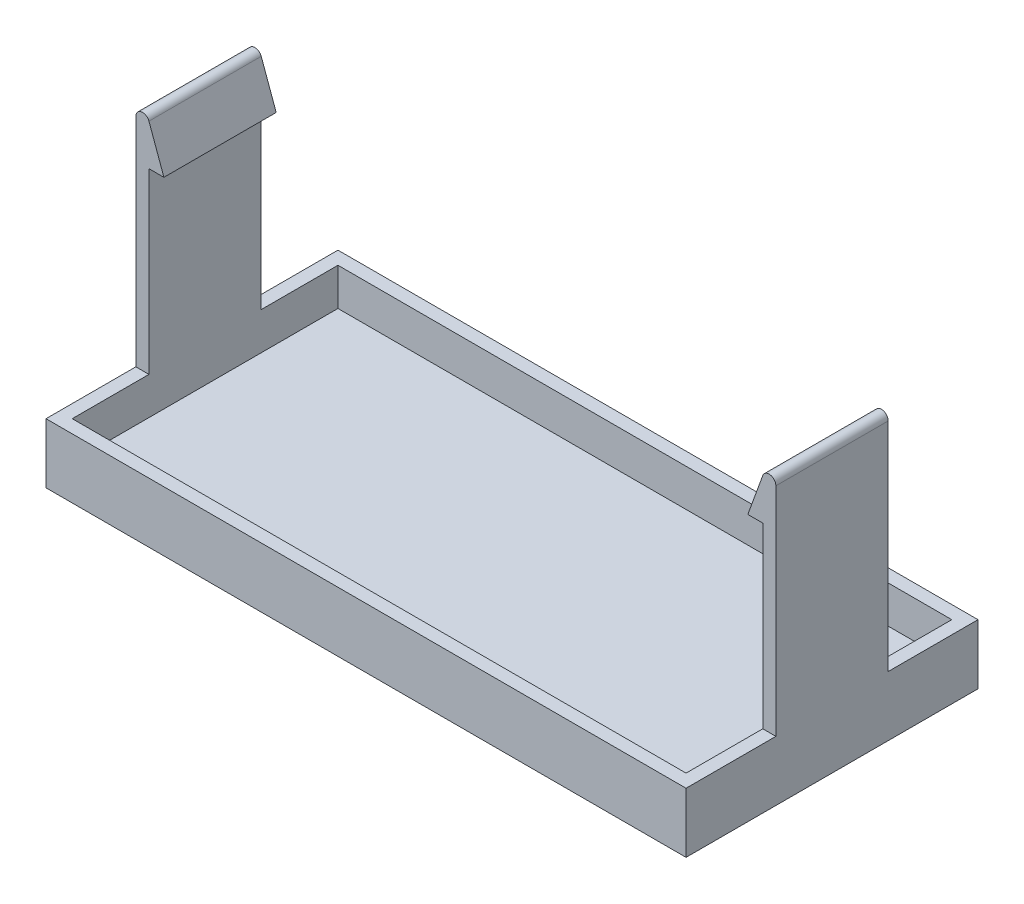
SolidWorks part; units mm, degrees
ref_plane "Front Plane" through (0, 0, 0) normal (0, 0, 1) x (1, 0, 0)
ref_plane "Top Plane" through (0, 0, 0) normal (0, 1, 0) x (1, 0, 0)
ref_plane "Right Plane" through (0, 0, 0) normal (1, 0, 0) x (0, 0, -1)
sketch "Sketch1" plane through (0, 0, 0) normal (0, 1, 0) x (1, 0, 0)
  line L1 (0, 0) -> (85.5, 0)
  line L2 (0, 0) -> (0, 39)
  line L3 (0, 39) -> (85.5, 39)
  line L4 (85.5, 0) -> (85.5, 39)
  dimension "D1" = 39
  dimension "D2" = 85.5
extrude "Boss-Extrude1" add sketch "Sketch1" along normal blind 3
sketch "Sketch2" plane through (0, 3, 0) normal (0, 1, 0) x (1, 0, 0)
  line L0 (42.75, 1.75) -> (42.75, 0) construction
  line L1 (1.75, 37.25) -> (83.75, 37.25)
  line L2 (1.75, 37.25) -> (1.75, 1.75)
  line L3 (1.75, 1.75) -> (83.75, 1.75)
  line L4 (83.75, 37.25) -> (83.75, 1.75)
  line L5 (0, 0) -> (85.5, 0) construction
  line L6 (1.75, 19.5) -> (0, 19.5) construction
  line L7 (0, 39) -> (0, 0) construction
  line L9 (0, 39) -> (85.5, 39)
  line L10 (0, 39) -> (0, 0)
  line L11 (0, 0) -> (85.5, 0)
  line L12 (85.5, 39) -> (85.5, 0)
  dimension "D1" = 35.5
  dimension "D2" = 82
extrude "Boss-Extrude2" add sketch "Sketch2" along normal blind 5
sketch "Sketch3" plane through (0, 8, 0) normal (0, 1, 0) x (1, 0, 0)
  line L0 (42.75, 39) -> (42.75, 0) construction
  line L1 (85.5, 39) -> (0, 39) construction
  line L2 (0, 0) -> (85.5, 0) construction
  line L3 (0, 39) -> (0, 0) construction
  line L4 (0, 27) -> (1.75, 27)
  line L5 (0, 27) -> (0, 12)
  line L6 (0, 12) -> (1.75, 12)
  line L7 (1.75, 27) -> (1.75, 12)
  line L8 (1.75, 37.25) -> (1.75, 1.75) construction
  line L9 (83.75, 27) -> (83.75, 12)
  line L10 (85.5, 27) -> (83.75, 27)
  line L11 (85.5, 27) -> (85.5, 12)
  line L12 (85.5, 12) -> (83.75, 12)
  point P14 (0, 19.5)
  point P15 (0, 0)
  point P16 (0, 0)
  dimension "D1" = 15
extrude "Boss-Extrude3" add sketch "Sketch3" along normal blind 23.8
sketch "Sketch4" plane through (0, 0, -12) normal (0, 0, 1) x (1, 0, 0)
  line L0 (1.75, 31.8) -> (3.75, 31.8)
  line L1 (3.75, 31.8) -> (1.75, 37.295)
  line L2 (0, 36.9864) -> (0, 31.8)
  line L3 (42.75, -22.6952) -> (42.75, -11.7345) construction
  line L6 (83.75, 3) -> (1.75, 3) construction
  line L7 (1.75, 31.8) -> (1.75, 8) construction
  line L8 (1.75, 31.8) -> (0, 31.8)
  line L9 (83.75, 31.8) -> (85.5, 31.8)
  line L10 (85.5, 36.9864) -> (85.5, 31.8)
  line L11 (81.75, 31.8) -> (83.75, 37.295)
  line L12 (83.75, 31.8) -> (81.75, 31.8)
  arc A0 (1.75, 37.295) -> (0, 36.9864) centre (0.9022, 36.9864) ccw
  arc A1 (83.75, 37.295) -> (85.5, 36.9864) centre (84.5978, 36.9864) cw
  point P12 (42.75, 3)
  dimension "D1" = 2
  dimension "D2" = 20
extrude "Boss-Extrude4" add sketch "Sketch4" against normal up to surface (15 mm away) up to face at (0.875, 19.9, -27)
